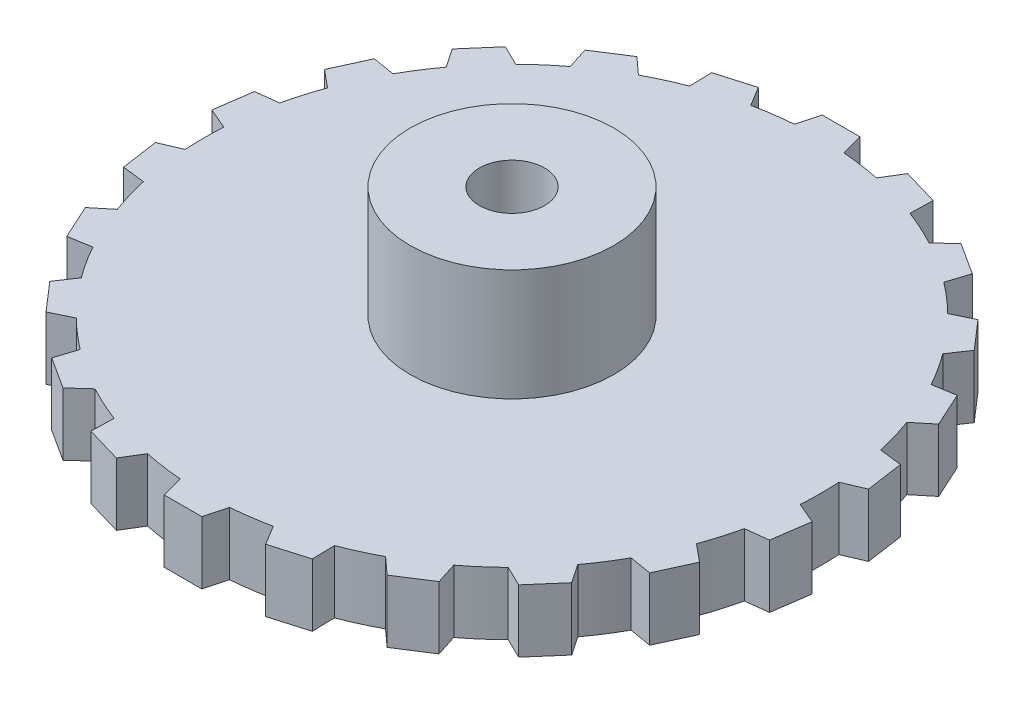
SolidWorks part; units mm, degrees
ref_plane "Front Plane" through (0, 0, 0) normal (0, 0, 1) x (1, 0, 0)
ref_plane "Top Plane" through (0, 0, 0) normal (0, 1, 0) x (1, 0, 0)
ref_plane "Right Plane" through (0, 0, 0) normal (1, 0, 0) x (0, 0, -1)
sketch "Sketch1" plane through (0, 0, 0) normal (0, 1, 0) x (1, 0, 0)
  circle A0 centre (0, 0) radius 29.5
  dimension "D1" = 59
extrude "Boss-Extrude3" add sketch "Sketch1" along normal blind 6
sketch "Sketch2" plane through (0, 6, 0) normal (0, 1, 0) x (1, 0, 0)
  line L0 (0, 0) -> (0, 62.0758) construction
  line L1 (0, 31.5) -> (1.8, 31.5)
  line L2 (1.8, 31.5) -> (3.4077, 25.5)
  line L3 (3.4077, 25.5) -> (0, 25.5)
  line L4 (0, 25.5) -> (-3.4077, 25.5)
  line L5 (-3.4077, 25.5) -> (-1.8, 31.5)
  line L6 (-1.8, 31.5) -> (0, 31.5)
  dimension "D1" = 1.8
  dimension "D2" = 1.8
  dimension "D3" = 75
  dimension "D4" = 75
  dimension "D5" = 31.5
extrude "Boss-Extrude2" add sketch "Sketch2" against normal blind 6
pattern_circular "CirPattern3" count 22 over 360 about axis through (0, 0, 0) along (0, 1, 0) of "Boss-Extrude2"
sketch "Sketch5" plane through (0, 6, 0) normal (0, 1, 0) x (1, 0, 0)
  circle A0 centre (0, 0) radius 9.75
  dimension "D1" = 19.5
extrude "Boss-Extrude4" add sketch "Sketch5" along normal blind 10.7
sketch "Sketch6" plane through (0, 16.7, 0) normal (0, 1, 0) x (1, 0, 0)
  circle A0 centre (0, 0) radius 3.125
  dimension "D1" = 6.25
extrude "Cut-Extrude1" cut sketch "Sketch6" against normal through all
